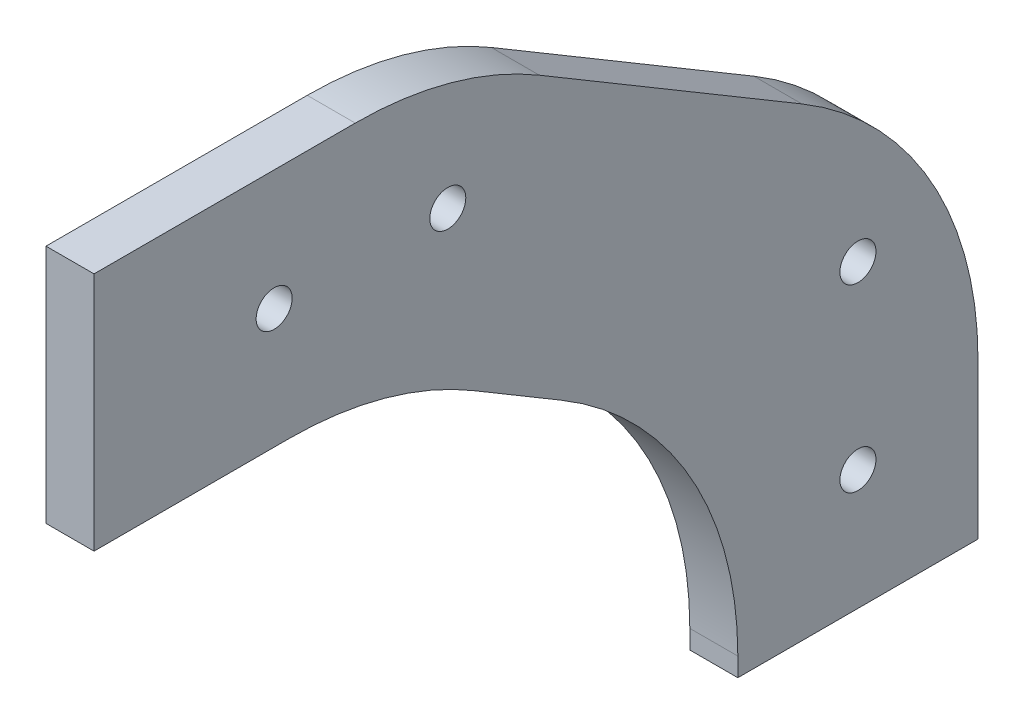
SolidWorks part; units mm, degrees
ref_plane "Alzado" through (0, 0, 0) normal (0, 0, 1) x (1, 0, 0)
ref_plane "Planta" through (0, 0, 0) normal (0, 1, 0) x (1, 0, 0)
ref_plane "Vista lateral" through (0, 0, 0) normal (1, 0, 0) x (0, 0, -1)
sketch "Croquis1" plane through (0, 0, 0) normal (1, 0, 0) x (0, 0, -1)
  line L0 (45.4996, 10) -> (75.4996, 10)
  line L1 (70.0022, -10) -> (99.1176, -27.314)
  line L2 (70.0022, -10) -> (45.4996, -10)
  line L3 (75.4996, 10) -> (119.1176, -15.9382)
  line L4 (80.2247, 7.1902) -> (127.9733, -21.2044) construction
  line L5 (45.4996, -10) -> (45.4996, 10)
  line L6 (99.1176, -27.314) -> (99.1176, -45.9382)
  line L7 (70.0022, -10) -> (117.7508, -38.3946) construction
  line L8 (119.1176, -15.9382) -> (119.1176, -45.9382)
  line L9 (119.1176, -27.314) -> (119.1176, -45.9382) construction
  line L10 (119.1176, -45.9382) -> (99.1176, -45.9382)
  dimension "D1" = 20
  dimension "D2" = 30
  dimension "D3" = 30
  dimension "D5" = 20
extrude "Saliente-Extruir1" add sketch "Croquis1" along normal blind 4
fillet "Redondeo1" radius 30 4 edges at (2, -27.314, -99.1176) (2, -15.9382, -119.1176) (2, -10, -70.0022) (2, 10, -75.4996)
sketch "Croquis2" plane through (4, 0, 0) normal (1, 0, 0) x (0, 0, -1)
  circle A0 centre (60.4996, 0) radius 1.5
  circle A1 centre (74.96, 0) radius 1.5
extrude "Cortar-Extruir1" cut sketch "Croquis2" against normal blind 50
sketch "Croquis3" plane through (4, 0, 0) normal (1, 0, 0) x (0, 0, -1)
  line L0 (109.1176, -45.9382) -> (109.1176, 0) construction
  line L1 (99.1176, -45.9382) -> (119.1176, -45.9382) construction
  circle A0 centre (109.1176, -35.9382) radius 1.5
  circle A1 centre (109.1176, -20.9382) radius 1.5
  dimension "D1" = 10
  dimension "D3" = 3
  dimension "D4" = 3
  dimension "D2" = 15
extrude "Cortar-Extruir2" cut sketch "Croquis3" against normal blind 10
